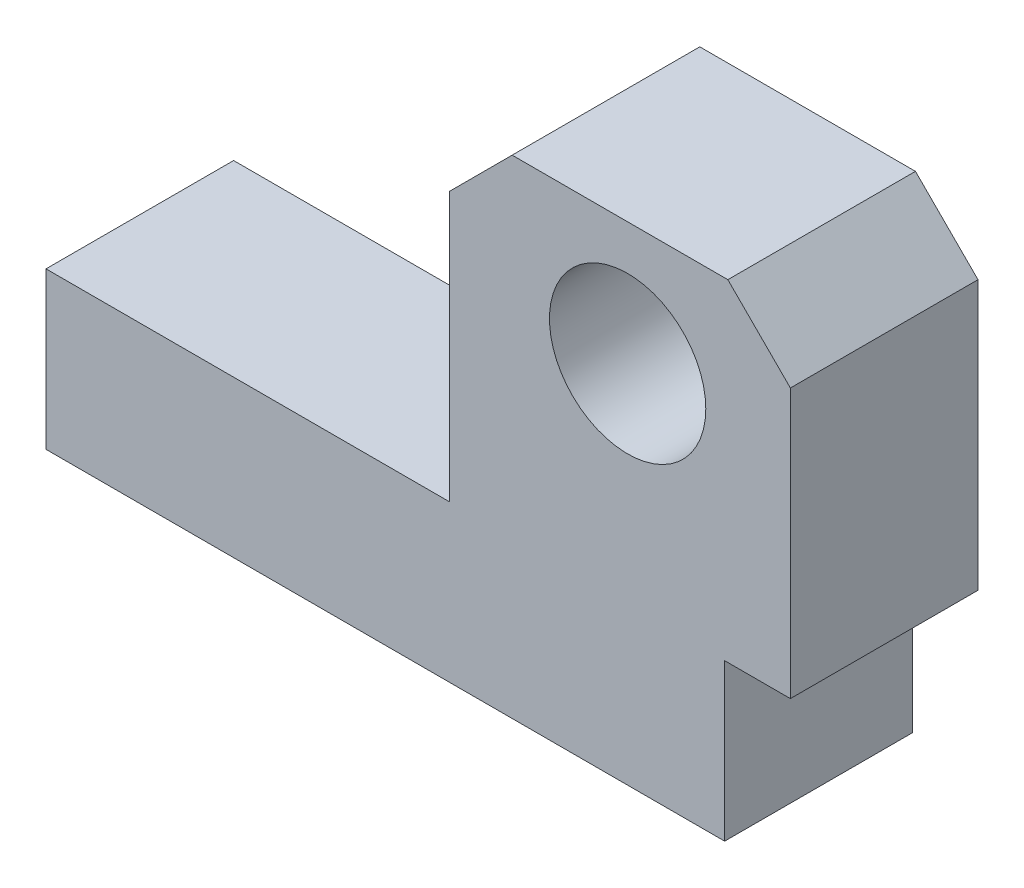
SolidWorks part; units mm, degrees
ref_plane "Спереди" through (0, 0, 0) normal (0, 0, 1) x (1, 0, 0)
ref_plane "Сверху" through (0, 0, 0) normal (0, 1, 0) x (1, 0, 0)
ref_plane "Справа" through (0, 0, 0) normal (1, 0, 0) x (0, 0, -1)
sketch "Эскиз1" plane through (0, 0, 0) normal (0, 0, 1) x (1, 0, 0)
  line L0 (-4.7304, 5) -> (8.1773, 5)
  line L1 (-4.7304, 0) -> (16.9727, 0)
  line L2 (-4.7304, 0) -> (-4.7304, 5)
  line L3 (10.1773, 15.603) -> (17.0753, 15.603)
  line L4 (19.0753, 5) -> (19.0753, 13.603)
  line L5 (8.1773, 5) -> (8.1773, 13.603)
  line L6 (-30.1123, 0) -> (34.8877, 0) construction
  line L7 (8.1773, 13.603) -> (10.1773, 15.603)
  line L8 (17.0753, 15.603) -> (19.0753, 13.603)
  line L9 (16.9727, 0) -> (16.9727, 5)
  line L10 (16.9727, 5) -> (19.0753, 5)
  circle A0 centre (13.8703, 11.6742) radius 2.5
  point P1 (8.1773, 15.603)
  point P7 (19.0753, 15.603)
  dimension "D1" = 5
extrude "Вытянуть1" add sketch "Эскиз1" along normal blind 6
